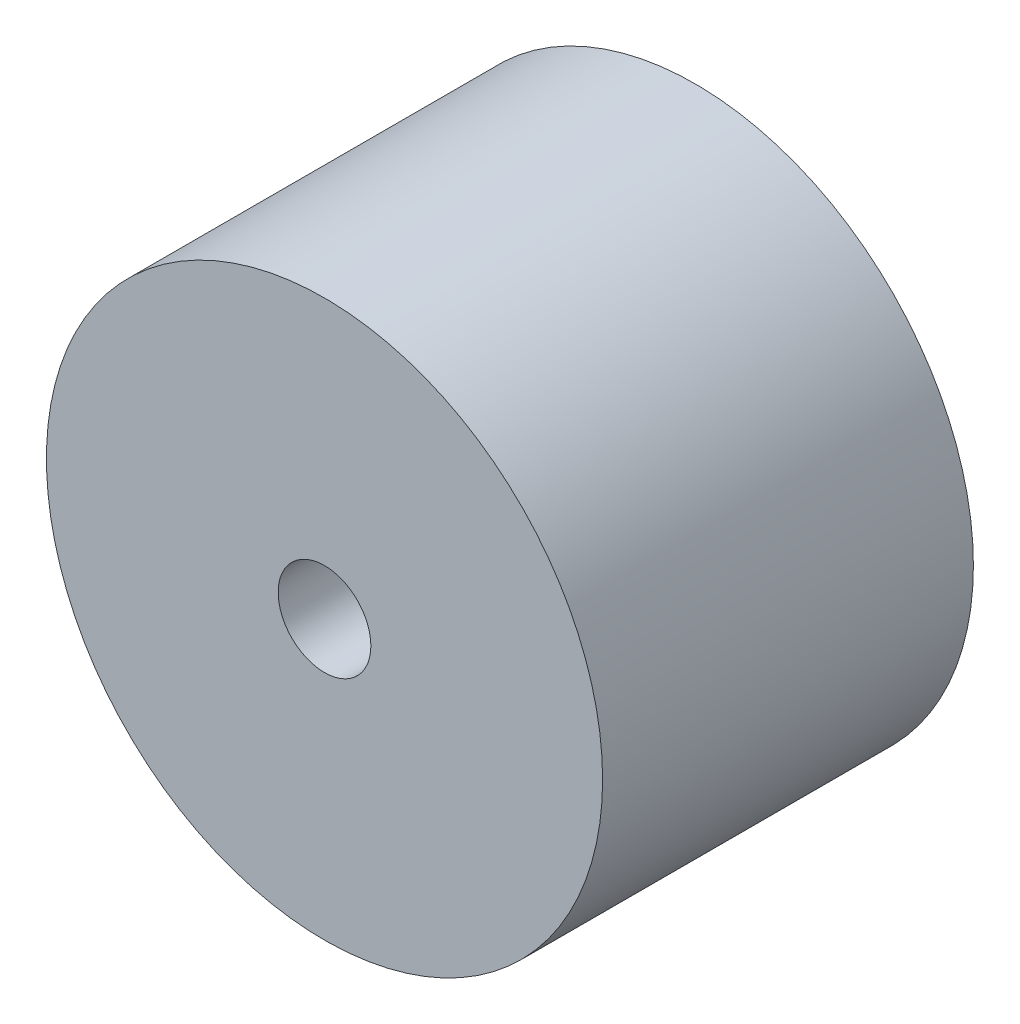
SolidWorks part; units mm, degrees
ref_plane "前视基准面" through (0, 0, 0) normal (0, 0, 1) x (1, 0, 0)
ref_plane "上视基准面" through (0, 0, 0) normal (0, 1, 0) x (1, 0, 0)
ref_plane "右视基准面" through (0, 0, 0) normal (1, 0, 0) x (0, 0, -1)
other "Configuration Table"
sketch "草图1" plane through (0, 0, 0) normal (0, 0, 1) x (1, 0, 0)
  circle A0 centre (0, 0) radius 18
  circle A1 centre (0, 0) radius 3
extrude "凸台-拉伸1" add sketch "草图1" along normal blind 24
